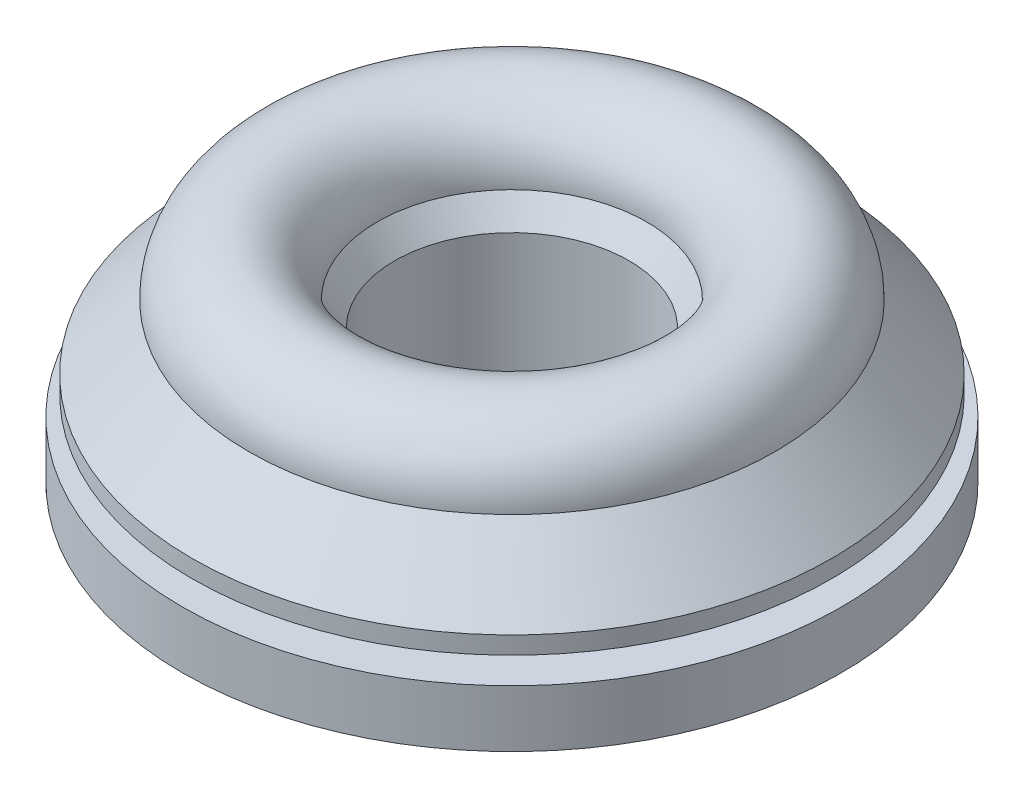
SolidWorks part; units mm, degrees
material "Rubber"
ref_plane "Front" through (0, 0, 0) normal (0, 0, 1) x (1, 0, 0)
ref_plane "Top" through (0, 0, 0) normal (0, 1, 0) x (1, 0, 0)
ref_plane "Right" through (0, 0, 0) normal (1, 0, 0) x (0, 0, -1)
sketch "Sketch1" plane through (0, 0, 0) normal (0, 0, 1) x (1, 0, 0)
  line L0 (-21.4312, 0) -> (21.4312, 0) construction
  line L1 (0, 10.1346) -> (0, -4.3434) construction
  line L2 (-7.62, 0) -> (7.62, 0) construction
  line L3 (21.4312, 0.635) -> (21.4312, -0.635) construction
  line L4 (8.763, 5.9563) -> (7.62, 4.3434)
  line L5 (21.4312, -0.635) -> (17.4625, -0.635)
  line L6 (0, 10.1346) -> (21.4312, 10.1346) construction
  line L7 (17.4625, -0.635) -> (17.4625, 0.635)
  line L8 (17.4625, 0.635) -> (20.7963, 0.635)
  line L9 (20.7963, 0.635) -> (20.7963, 1.778)
  line L10 (20.7963, 1.778) -> (17.1196, 5.9563)
  line L11 (21.4312, -0.635) -> (21.4312, -4.3434)
  line L12 (7.62, -4.3434) -> (21.4312, -4.3434)
  line L13 (8.763, 5.9563) -> (17.1196, 5.9563) construction
  line L14 (12.9413, 5.9563) -> (12.9413, 10.1346) construction
  line L15 (17.1196, 5.9563) -> (17.1196, 1.778) construction
  line L16 (17.1196, 1.778) -> (20.7963, 1.778) construction
  line L17 (7.62, -4.3434) -> (7.62, 4.3434)
  line L18 (-17.4625, 0) -> (17.4625, 0) construction
  arc A0 (17.1196, 5.9563) -> (8.763, 5.9563) centre (12.9413, 5.9563) ccw
  dimension "Flange Dia" = 42.8625
  dimension "Overall Ht" = 14.478
  dimension "ID" = 15.24
  dimension "for material thickness" = 1.27
  dimension "D2" = 1.143
  dimension "D5" = 0.635
  dimension "D3" = 4.3434
  dimension "D4" = 1.143
  dimension "For Hole Dia" = 34.925
revolve "Revolve1" add sketch "Sketch1" angle 360 about L1
ref_plane "Plane1" [suppressed] through (0, 8.89, 0) normal (0, -1, 0) x (1, 0, 0)
sketch "Sketch2" [suppressed] plane through (0, 8.89, 0) normal (0, -1, 0) x (1, 0, 0)
  circle A0 centre (0, 0) radius 3.81 construction
equation "\"D2@Sketch1\"=\"for material thickness@Sketch1\"*.9"
equation "\"D3@Sketch1\"=\"Overall Ht@Sketch1\"*.3"
equation "\"D4@Sketch1\"=\"D2@Sketch1\""
